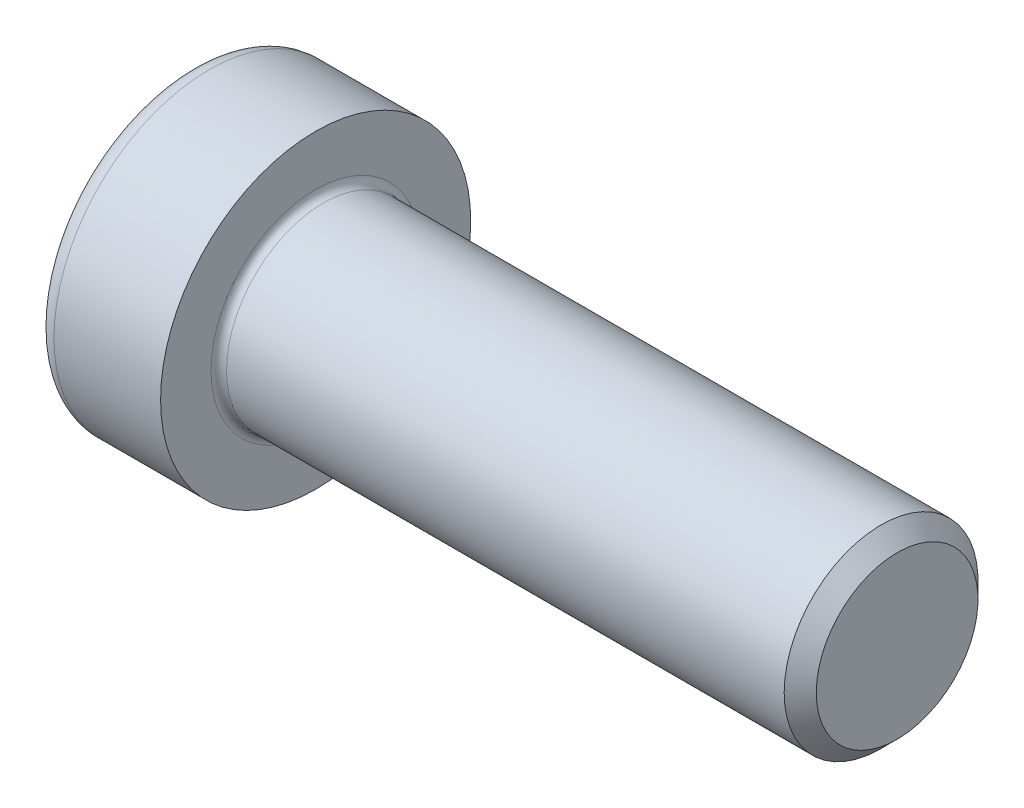
SolidWorks part; units mm, degrees
revolve "Base-Revolve" add sketch "BodySke"
sketch "BodySke" plane through (0, 0, 0) normal (0, 0, 1) x (1, 0, 0)
  line L0 (0, 0) -> (0, 8)
  line L1 (0, 8) -> (6.5, 8)
  line L2 (6.5, 8) -> (6.5, 5)
  line L3 (6.5, 5) -> (35.672, 5)
  line L4 (36.5, 4.172) -> (36.5, 0)
  line L5 (36.5, 0) -> (0, 0)
  line L6 (-31.75, 0) -> (127, 0) construction
  line L8 (36.5, 4.172) -> (35.672, 5)
  line L10 (36.5, -4.172) -> (35.672, -5) construction
  line L11 (8, 4.525) -> (8, -1.825) construction
  line L12 (6.5, 4.525) -> (6.5, -1.825) construction
  line L13 (-23.5, 4.525) -> (-23.5, -1.825) construction
  dimension "Head_ht" = 6.5
  dimension "Length" = 30
  dimension "Body_ch_ang" = 45
  dimension "Diameter" = 10
  dimension "Minor_dia" = 8.344
  dimension "Advance" = 1.5
  dimension "Thread_nom" = 30
  dimension "Thread_length" = 60
  dimension "Head_dia" = 16
cosmetic thread "ThreadCosmetic" [suppressed]
fillet "Fillet1" radius 0.4 1 edges at (6.5, 0, 5)
fillet "Fillet2" radius 1 1 edges at (0, 0, 8)
ref_plane "Plane1" through (0, 0, 0) normal (0, 0, 1) x (1, 0, 0)
ref_plane "Plane2" through (0, 0, 0) normal (0, 1, 0) x (1, 0, 0)
ref_plane "Plane3" through (0, 0, 0) normal (1, 0, 0) x (0, 0, -1)
sketch "HexSke" plane through (0, 0, 0) normal (-1, 0, 0) x (0, 0.5, 0.866)
  line L0 (2.3599, 4.0875) -> (-2.3599, 4.0875)
  line L1 (-2.3599, 4.0875) -> (-4.7198, 0)
  line L2 (2.3599, 4.0875) -> (4.7198, 0)
  line L3 (2.3599, -4.0875) -> (4.7198, 0)
  line L4 (2.3599, -4.0875) -> (-2.3599, -4.0875)
  line L5 (-2.3599, -4.0875) -> (-4.7198, 0)
  dimension "D1" = 4.0875
  dimension "D2" = 4.0875
  dimension "Hex_size" = 8.175
extrude "Hex" cut sketch "HexSke" against normal blind 3.65
sketch "PilotSke" plane through (0, 0, 0) normal (0, 0, 1) x (1, 0, 0)
  line L0 (0, 4.0875) -> (3.65, 4.0875)
  line L1 (3.65, 4.0875) -> (4.5449, 2.5375)
  line L2 (-31.75, 0) -> (127, 0) construction
  line L3 (9.325, 0) -> (0, 0)
  line L4 (0, 0) -> (0, 4.0875)
  line L5 (4.5449, 2.5375) -> (7.86, 2.5375)
  line L6 (0, 0) -> (47.625, 0) construction
  line L7 (7.86, 2.5375) -> (9.325, 0)
  dimension "D1" = 4.0875
  dimension "D2" = 60
  dimension "Depth" = 3.65
  dimension "Pilot_dia" = 5.075
  dimension "Pilot_Depth" = 7.86
revolve "Hex-PreBroach" cut sketch "PilotSke" angle 360 about L6
sketch "ThdSchSke" plane through (0, 0, 0) normal (0, 0, 1) x (1, 0, 0)
  line L0 (11, -4.172) -> (10.4202, -5)
  line L1 (11, -4.172) -> (11.5798, -5)
  line L2 (11.5798, -5) -> (11.5798, -6.25)
  line L3 (-3.175, 0) -> (5.1513, 0) construction
  line L4 (0, 7) -> (0, -7) construction
  line L5 (11.5798, -6.25) -> (10.4202, -6.25)
  line L6 (10.4202, -6.25) -> (10.4202, -5)
  dimension "Thread_minor" = 8.344
  dimension "Diameter" = 10
  dimension "Start" = 11
revolve "ThreadSchematic" [suppressed] cut sketch "ThdSchSke" angle 360 about L3
pattern_linear "ThdSchPat" [suppressed]
equation "\"D2@HexSke\" = \"Hex_size@HexSke\" / 2"
equation "\"D1@HexSke\" = \"Hex_size@HexSke\" / 2"
equation "\"D1@PilotSke\" = \"Hex_size@HexSke\" / 2"
equation "\"Thread_minor@ThreadCosmetic\"  =  \"Minor_dia@BodySke\""
equation "\"Depth@PilotSke\" =  \"Key_eng@Hex\""
equation "\"Thread_length@ThreadCosmetic\" = ((sgn( (\"Length@BodySke\" - \"Advance@BodySke\" * 3.0) - \"Thread_nom@BodySke\" )-1)*( (\"Length@BodySke\" - \"Advance@BodySke\" * 3.0) - \"Thread_nom@BodySke\" ))/-2+ \"Thread_nom@BodySke\""
equation "\"Thread_minor@ThdSchSke\" = \"Minor_dia@BodySke\""
equation "\"Diameter@ThdSchSke\" = \"Diameter@BodySke\""
equation "\"Overcut@ThdSchSke\" = \"Diameter@BodySke\" * 1.25"
equation "\"Start@ThdSchSke\" = \"Head_ht@BodySke\" + \"Length@BodySke\" - \"Thread_length@ThreadCosmetic\"  '---Non-countersunk---"
equation "\"Num_threads@ThdSchPat\" = int( \"Thread_length@ThreadCosmetic\" / \"Advance@BodySke\" + 0.999 )  + 1"
equation "\"Advance@ThdSchPat\" = \"Thread_length@ThreadCosmetic\" /  (\"Num_threads@ThdSchPat\" - 1) 'relax it"
equation "\"Num_threads@ThdSchPat\" = \"Num_threads@ThdSchPat\" - sgn( \"Num_threads@ThdSchPat\" - 1) '---chamfered tips only---"
